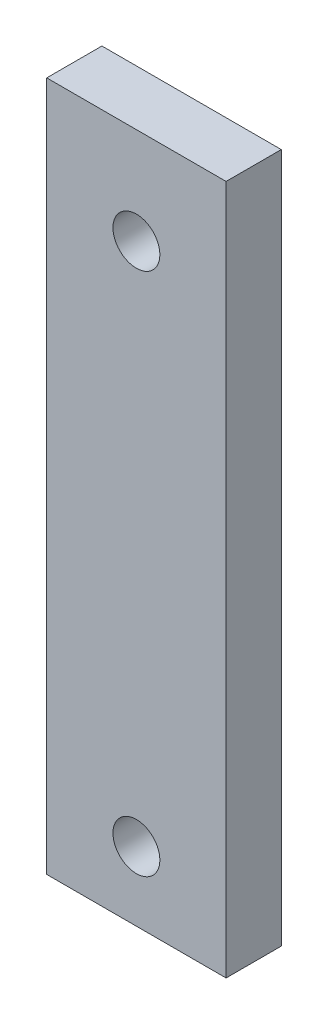
SolidWorks part; units mm, degrees
ref_plane "Front Plane" through (0, 0, 0) normal (0, 0, 1) x (1, 0, 0)
ref_plane "Top Plane" through (0, 0, 0) normal (0, 1, 0) x (1, 0, 0)
ref_plane "Right Plane" through (0, 0, 0) normal (1, 0, 0) x (0, 0, -1)
sketch "Sketch1" plane through (0, 0, 0) normal (0, 0, 1) x (1, 0, 0)
  line L1 (-32.5, 125) -> (32.5, 125)
  line L2 (-32.5, 125) -> (-32.5, -125)
  line L3 (-32.5, -125) -> (32.5, -125)
  line L4 (32.5, 125) -> (32.5, -125)
  line L5 (-32.5, 125) -> (32.5, -125) construction
  line L6 (-32.5, -125) -> (32.5, 125) construction
  point P0 (0, 0)
extrude "Boss-Extrude1" add sketch "Sketch1" along normal blind 20
sketch "Sketch3" plane through (0, 0, 0) normal (0, 0, 1) x (1, 0, 0)
  circle A0 centre (0, -100) radius 8.5
  circle A1 centre (0, 90) radius 8.5
extrude "Cut-Extrude2" cut sketch "Sketch3" along normal blind 28
